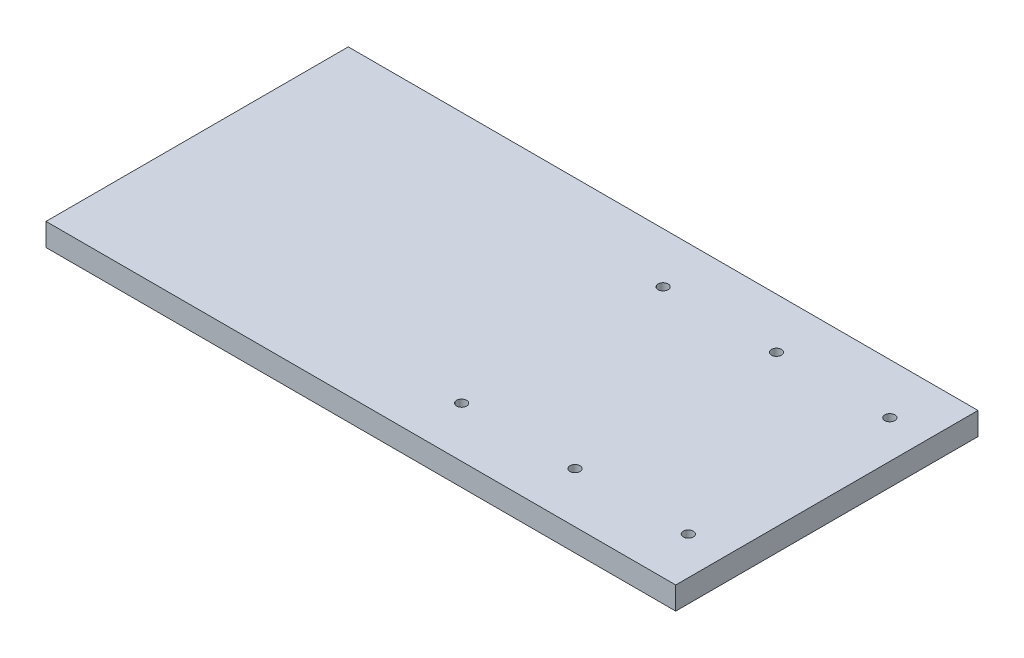
SolidWorks part; units mm, degrees
material "Клен"
ref_plane "Спереди" through (0, 0, 0) normal (0, 0, 1) x (1, 0, 0)
ref_plane "Сверху" through (0, 0, 0) normal (0, 1, 0) x (1, 0, 0)
ref_plane "Справа" through (0, 0, 0) normal (1, 0, 0) x (0, 0, -1)
sketch "Эскиз1" plane through (0, 0, 0) normal (0, 1, 0) x (1, 0, 0)
  line L0 (0, 200) -> (500, 200) construction
  line L1 (0, 0) -> (500, 0)
  line L2 (0, 0) -> (0, 240)
  line L3 (0, 240) -> (500, 240)
  line L4 (500, 0) -> (500, 240)
  line L5 (0, 40) -> (500, 40) construction
  circle A0 centre (470, 200) radius 4
  circle A1 centre (380, 200) radius 4
  circle A2 centre (290, 200) radius 4
  circle A3 centre (470, 40) radius 4
  circle A4 centre (380, 40) radius 4
  circle A5 centre (290, 40) radius 4
  dimension "D4" = 40
  dimension "D5" = 8
  dimension "D7" = 8
  dimension "D6" = 8
  dimension "D8" = 8
  dimension "D9" = 8
  dimension "D10" = 8
  dimension "D1" = 240
  dimension "D2" = 500
  dimension "D3" = 40
  dimension "D11" = 30
  dimension "D12" = 90
  dimension "D13" = 90
  dimension "D14" = 30
  dimension "D15" = 90
  dimension "D16" = 90
extrude "Бобышка-Вытянуть1" add sketch "Эскиз1" along normal blind 18
